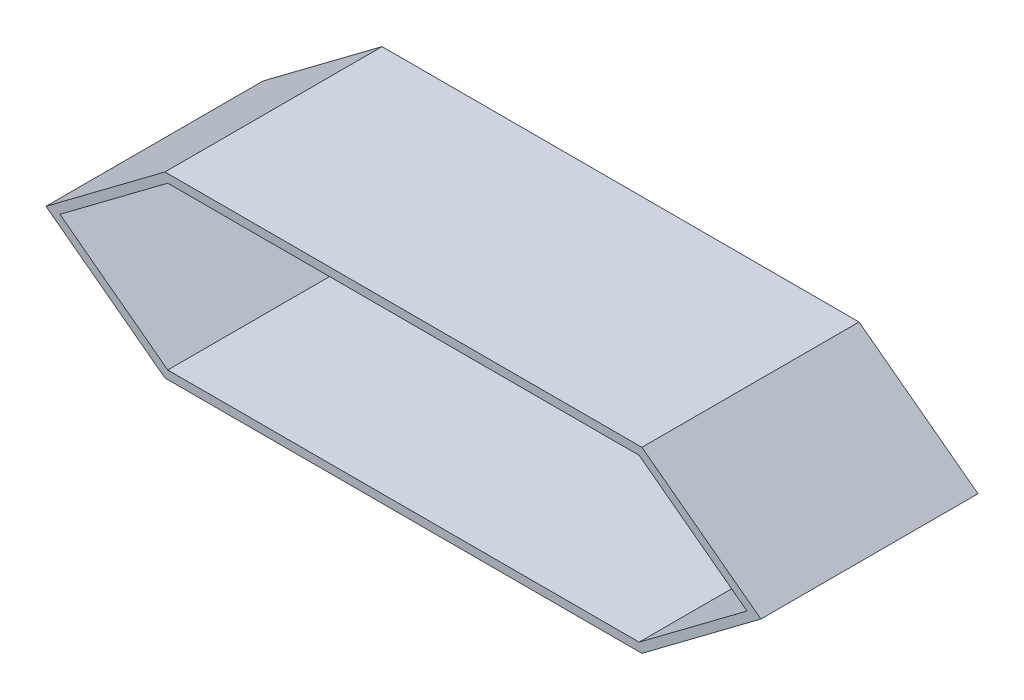
SolidWorks part; units mm, degrees
ref_plane "Plan de face" through (0, 0, 0) normal (0, 0, 1) x (1, 0, 0)
ref_plane "Plan de dessus" through (0, 0, 0) normal (0, 1, 0) x (1, 0, 0)
ref_plane "Plan de droite" through (0, 0, 0) normal (1, 0, 0) x (0, 0, -1)
sketch "Esquisse1" plane through (0, 0, 0) normal (0, 0, 1) x (1, 0, 0)
  line L0 (0, 0) -> (0, 71.2253) construction
  line L1 (22.85, 64.9041) -> (-22.85, 64.9041)
  line L2 (-22.85, 64.9041) -> (-34.25, 56.3541)
  line L3 (-34.25, 56.3541) -> (0, 56.3541) construction
  line L4 (-22.85, 47.8041) -> (-34.25, 56.3541)
  line L5 (22.85, 47.8041) -> (-22.85, 47.8041)
  line L6 (22.85, 47.8041) -> (34.25, 56.3541)
  line L7 (22.85, 64.9041) -> (34.25, 56.3541)
  point P10 (0, 47.8041)
  point P12 (0, 64.9041)
  dimension "D1" = 11.4
  dimension "D2" = 8.55
  dimension "D3" = 34.25
extrude "Boss.-Extru.1" add sketch "Esquisse1" along normal blind 0.8
sketch "Esquisse2" plane through (0, 0, 0.8) normal (0, 0, 1) x (1, 0, 0)
  line L0 (34.25, 56.3541) -> (22.85, 64.9041) construction
  line L1 (22.85, 47.8041) -> (34.25, 56.3541) construction
  line L2 (-22.85, 47.8041) -> (22.85, 47.8041) construction
  line L3 (-34.25, 56.3541) -> (-22.85, 47.8041) construction
  line L4 (-22.85, 64.9041) -> (-34.25, 56.3541) construction
  line L5 (22.85, 64.9041) -> (-22.85, 64.9041) construction
  line L6 (34.25, 56.3541) -> (22.85, 64.9041)
  line L7 (22.85, 47.8041) -> (34.25, 56.3541)
  line L8 (-22.85, 47.8041) -> (22.85, 47.8041)
  line L9 (-34.25, 56.3541) -> (-22.85, 47.8041)
  line L10 (-22.85, 64.9041) -> (-34.25, 56.3541)
  line L11 (22.85, 64.9041) -> (-22.85, 64.9041)
  line L12 (-22.5833, 64.1041) -> (-32.9167, 56.3541)
  line L13 (-32.9167, 56.3541) -> (-22.5833, 48.6041)
  line L14 (-22.5833, 48.6041) -> (22.5833, 48.6041)
  line L15 (22.5833, 48.6041) -> (32.9167, 56.3541)
  line L16 (32.9167, 56.3541) -> (22.5833, 64.1041)
  line L17 (22.5833, 64.1041) -> (-22.5833, 64.1041)
  dimension "D1" = 0.8
extrude "Boss.-Extru.2" add sketch "Esquisse2" along normal blind 20
